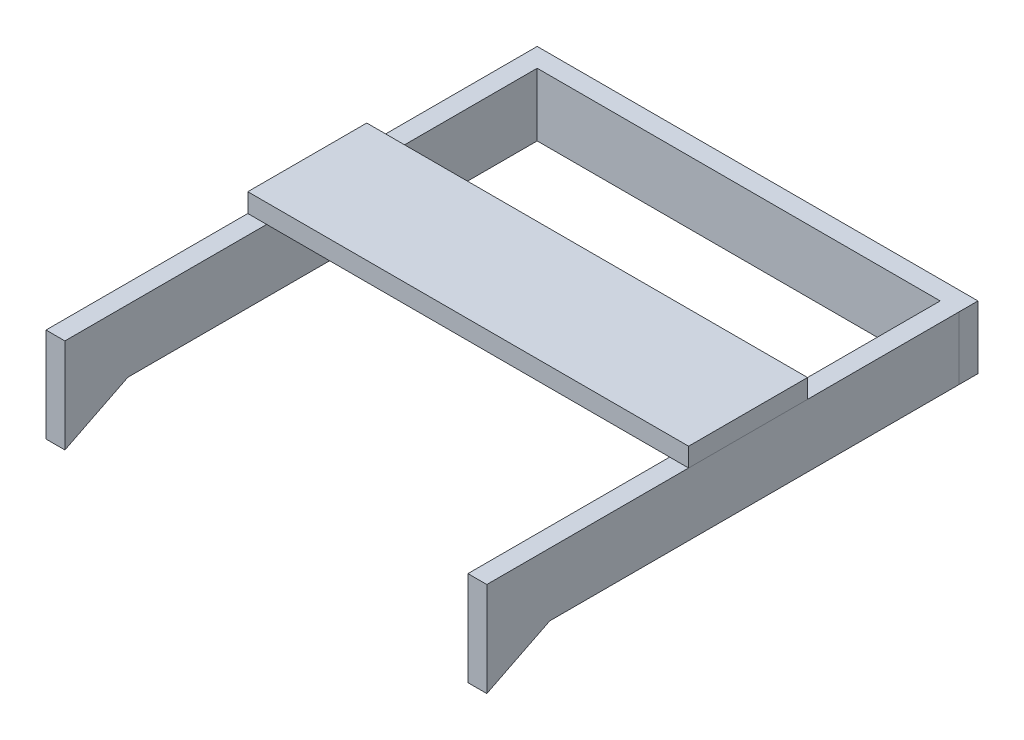
SolidWorks part; units mm, degrees
ref_plane "Top plane" through (0, 0, 0) normal (0, 0, 1) x (1, 0, 0)
ref_plane "Right plane" through (0, 0, 0) normal (0, 1, 0) x (1, 0, 0)
ref_plane "Front plane" through (0, 0, 0) normal (1, 0, 0) x (0, 0, -1)
sketch "Sketch1" plane through (0, 0, 0) normal (0, 0, 1) x (1, 0, 0)
  line L1 (48.092, -25.8134) -> (118.092, -25.8134)
  line L2 (48.092, -25.8134) -> (48.092, -40.8134)
  line L3 (48.092, -40.8134) -> (118.092, -40.8134)
  line L4 (118.092, -25.8134) -> (118.092, -40.8134)
  dimension "D1" = 15
  dimension "D2" = 70
extrude "Boss-Extrude1" add sketch "Sketch1" along normal blind 3
sketch "Sketch2" plane through (0, 0, 3) normal (0, 0, 1) x (1, 0, 0)
  line L0 (118.092, -25.8134) -> (48.092, -25.8134) construction
  line L1 (48.092, -25.8134) -> (51.092, -25.8134)
  line L2 (48.092, -25.8134) -> (48.092, -40.8134)
  line L3 (48.092, -40.8134) -> (51.092, -40.8134)
  line L4 (51.092, -25.8134) -> (51.092, -40.8134)
  line L5 (48.092, -40.8134) -> (118.092, -40.8134) construction
  line L7 (118.092, -25.8134) -> (115.092, -25.8134)
  line L8 (118.092, -25.8134) -> (118.092, -40.8134)
  line L9 (118.092, -40.8134) -> (115.092, -40.8134)
  line L10 (115.092, -25.8134) -> (115.092, -40.8134)
  dimension "D1" = 3
  dimension "3" = 3
extrude "Boss-Extrude2" add sketch "Sketch2" along normal blind 75
sketch "Sketch3" plane through (48.092, 0, 0) normal (-1, 0, 0) x (0, 0, 1)
  line L0 (78, -40.8134) -> (68, -35.8134)
  line L1 (68, -35.8134) -> (0, -35.8134)
  line L4 (0, -25.8134) -> (0, -40.8134)
  line L5 (0, -40.8134) -> (78, -40.8134)
  line L6 (78, -40.8134) -> (78, -25.8134)
  line L7 (78, -25.8134) -> (0, -25.8134)
  line L8 (0, -25.8134) -> (0, -40.8134)
  line L9 (0, -40.8134) -> (78, -40.8134)
  line L10 (78, -40.8134) -> (78, -25.8134)
  line L11 (78, -25.8134) -> (0, -25.8134)
  line M6 (0, -25.8134) -> (0, -40.8134)
  line M7 (0, -40.8134) -> (78, -40.8134)
  dimension "D2" = 5
  dimension "D3" = 10
  dimension "D1" = 0
extrude "Cut-Extrude1" cut sketch "Sketch3" against normal blind 75 contours L0 L1 M6 M7
sketch "Sketch4" plane through (0, -25.8134, 0) normal (0, 1, 0) x (1, 0, 0)
  line L0 (118.092, -78) -> (118.092, 0) construction
  line L1 (118.092, -27.0655) -> (48.092, -27.0655)
  line L2 (118.092, -27.0655) -> (118.092, -45.9576)
  line L3 (118.092, -45.9576) -> (48.092, -45.9576)
  line L4 (48.092, -27.0655) -> (48.092, -45.9576)
  line L5 (48.092, -78) -> (48.092, 0) construction
  point P8 (0, 0)
  point P9 (0, 0)
  point P10 (0, 0)
extrude "Boss-Extrude3" add sketch "Sketch4" along normal blind 3
sketch "Sketch5" plane through (48.092, 0, 0) normal (-1, 0, 0) x (0, 0, 1)
  line L0 (3, -25.8134) -> (3, -35.8134)
  line L1 (27.0655, -25.8134) -> (0, -25.8134) construction
  line L2 (68, -35.8134) -> (0, -35.8134) construction
  line L3 (78, -25.8134) -> (3, -25.8134)
  line L4 (78, -25.8134) -> (45.9576, -25.8134) construction
split line "Split Line1"
